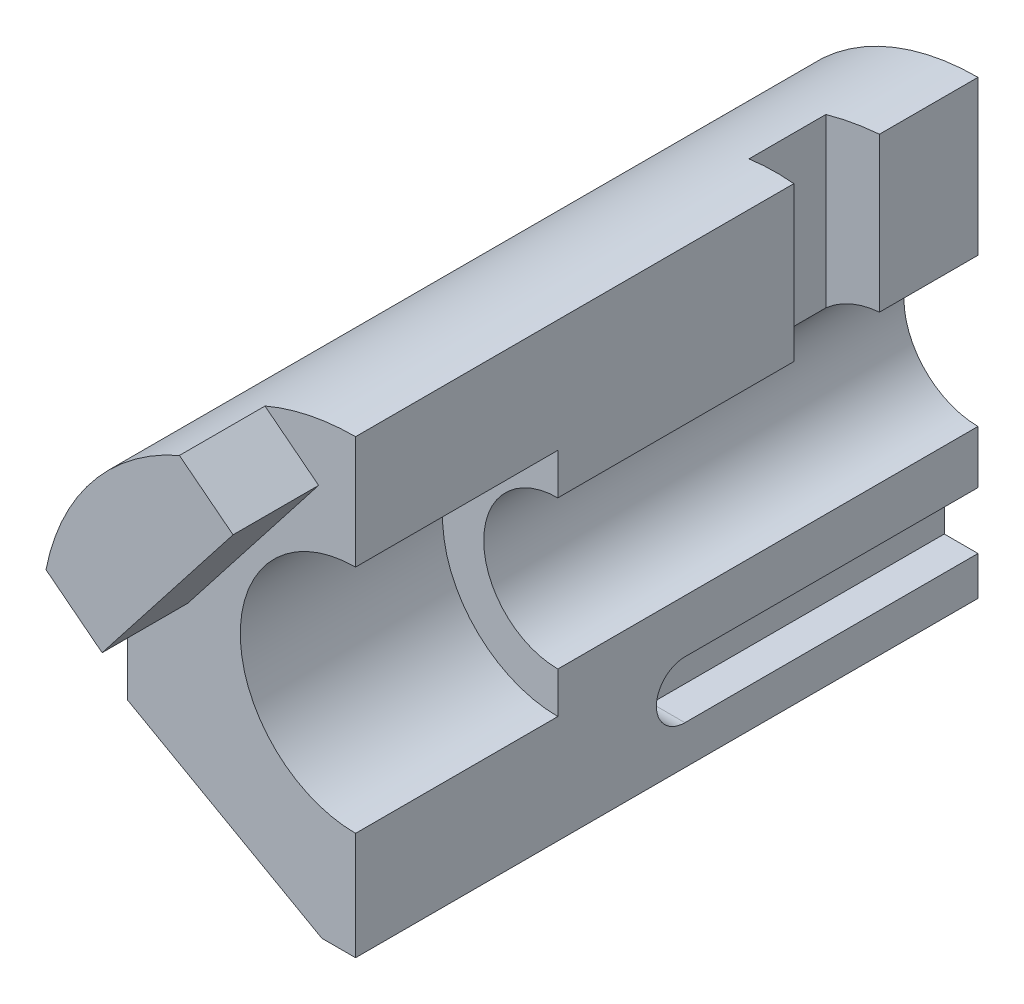
SolidWorks part; units mm, degrees
material "Alliage 1060"
ref_plane "Plan de face" through (0, 0, 0) normal (0, 0, 1) x (1, 0, 0)
ref_plane "Plan de dessus" through (0, 0, 0) normal (0, 1, 0) x (1, 0, 0)
ref_plane "Plan de droite" through (0, 0, 0) normal (1, 0, 0) x (0, 0, -1)
sketch "Esquisse1" plane through (0, 0, 0) normal (0, 0, 1) x (1, 0, 0)
  line L0 (0, -86) -> (0, 88)
  line L1 (0, -86) -> (-13, -86)
  line L5 (-88, 0) -> (-88, -43.8534)
  line L7 (-13, -86) -> (-88, -43.8534)
  arc A0 (0, 88) -> (-88, 0) centre (0, 0) ccw
  dimension "D1" = 176
  dimension "D2" = 13
extrude "Boss.-Extru.1" add sketch "Esquisse1" along normal blind 240
sketch "Esquisse2" plane through (0, 0, 240) normal (0, 0, 1) x (1, 0, 0)
  circle A0 centre (0, 0) radius 44.45
extrude "Enlèv. mat.-Extru.1" cut sketch "Esquisse2" against normal blind 78
sketch "Esquisse3" plane through (0, 0, 162) normal (0, 0, 1) x (1, 0, 0)
  line L0 (0, -44.45) -> (0, 44.45) construction
  circle A0 centre (0, 0) radius 28.575
extrude "Enlèv. mat.-Extru.2" cut sketch "Esquisse3" against normal through all
sketch "Esquisse7" plane through (0, 0, 240) normal (0, 0, 1) x (1, 0, 0)
  line L0 (0, 0) -> (-40.1885, 31.3987)
  line L1 (0, 0) -> (-155.8576, 0)
  line L2 (-14.2357, 64.6169) -> (-34.9181, 80.7758)
  line L3 (-64.7199, 0) -> (-14.2357, 64.6169)
  line L4 (-64.7199, 0) -> (-86.3605, 16.9075)
  arc A0 (0, 88) -> (-88, 0) centre (0, 0) ccw construction
  arc A1 (-34.9181, 80.7758) -> (-86.3605, 16.9075) centre (0, 0) ccw
  arc M5 (0, 88) -> (-88, 0) centre (0, 0) ccw
  dimension "D1" = 38
  dimension "D2" = 38
  dimension "D3" = 90
  dimension "D4" = 82
extrude "Boss.-Extru.4" add sketch "Esquisse7" along normal blind 33 contours L4 L3 L2 M5
sketch "Esquisse8" plane through (0, 0, 0) normal (1, 0, 0) x (0, 0, -1)
  line L0 (-71, 94.336) -> (-71, 4.336)
  line L3 (-71, 4.336) -> (-38, 4.336)
  line L4 (-38, 4.336) -> (-38, 94.336)
  line L5 (-38, 94.336) -> (-71, 94.336)
  line L6 (0, 28.575) -> (0, 88) construction
  dimension "D1" = 38
  dimension "D2" = 33
  dimension "D3" = 90
extrude "Enlèv. mat.-Extru.4" cut sketch "Esquisse8" against normal blind 19 draft 5 contours L5 L0 L3 L4
sketch "Esquisse9" plane through (0, 0, 0) normal (1, 0, 0) x (0, 0, -1)
  line L0 (0, -60) -> (-113, -60)
  line L1 (0, -86) -> (0, -28.575) construction
  line L2 (-240, -86) -> (0, -86) construction
  line L3 (-113, -49) -> (0, -49)
  line L4 (-113, -71) -> (0, -71)
  line L5 (0, -71) -> (0, -49)
  arc A0 (-113, -49) -> (-113, -71) centre (-113, -60) ccw
  dimension "D1" = 26
  dimension "D2" = 113
extrude "Enlèv. mat.-Extru.5" cut sketch "Esquisse9" against normal blind 13
ref_plane "Plan1" [suppressed] through (-9.5, 86.9622, 0) normal (-0.1086, 0.9941, 0) x (0.9941, 0.1086, 0)
sketch "Esquisse12" [suppressed] plane through (-9.5, 86.9622, 0) normal (-0.1086, 0.9941, 0) x (0.9941, 0.1086, 0)
  line L0 (9.5565, -38) -> (-9.5565, -39.6722)
  line L1 (-9.5565, -38) -> (-9.5565, -71) construction
  line L2 (9.5565, -71) -> (-9.5565, -69.3278)
  line L3 (-9.5565, -38) -> (9.5565, -38) construction
  line L4 (9.5565, -71) -> (-9.5565, -71) construction
  line L5 (-9.5565, -38) -> (9.5565, -38)
  line L6 (-9.5565, -38) -> (-9.5565, -39.6722)
  line L7 (9.5565, -71) -> (-9.5565, -71)
  line L8 (-9.5565, -69.3278) -> (-9.5565, -71)
  dimension "D1" = 5
  dimension "D2" = 5
sketch "Esquisse13" [suppressed] plane through (0, 0, 38) normal (0, 0, 1) x (1, 0, 0)
  line L2 (-19, 85.9244) -> (-19, 21.3432)
  line L3 (0, 28.575) -> (0, 88)
  line L4 (-19, 85.9244) -> (-19, 21.3432)
  line L5 (0, 28.575) -> (0, 88)
  arc A2 (0, 28.575) -> (-19, 21.3432) centre (0, 0) ccw
  arc A3 (0, 88) -> (-19, 85.9244) centre (0, 0) ccw
  arc A4 (0, 28.575) -> (-19, 21.3432) centre (0, 0) ccw
  arc A5 (0, 88) -> (-19, 85.9244) centre (0, 0) ccw
  dimension "D1" = 0
ref_plane "Plan2" [suppressed] through (0, 88, 0) normal (0, -1, 0) x (0, 0, -1)
sketch "Esquisse17" [suppressed] plane through (0, 88, 0) normal (0, -1, 0) x (0, 0, -1)
  line L0 (-71, -19) -> (-71, 0) construction
  line L1 (-38, 0) -> (-38, -19) construction
  line L2 (-38, -19) -> (-71, -19) construction
  line L3 (-71, -19) -> (-71, 0)
  line L4 (-38, 0) -> (-38, -19)
  line L5 (-38, -19) -> (-39.6623, -19)
  line L6 (-38, 0) -> (-39.6623, -19)
  line L7 (-71, 0) -> (-69.3377, -19)
  line L8 (-69.3377, -19) -> (-71, -19)
  dimension "D1" = 5
  dimension "D2" = 5
extrude "Boss.-Extru.5" [suppressed] add sketch "Esquisse17" along normal up to vertex (116.575 mm away) contours L4 L5 L6 | L3 L7 L8
sketch "Esquisse18" [suppressed] plane through (0, 0, 38) normal (0, 0, -1) x (-1, 0, 0)
  line L0 (0, 21.3432) -> (19, 21.3432) construction
  line L1 (0, 21.3432) -> (0, 28.575) construction
  line L2 (0, 21.3432) -> (19, 21.3432)
  line L3 (0, 21.3432) -> (0, 28.575)
  arc A0 (19, 21.3432) -> (0, 28.575) centre (0, 0) ccw construction
  arc A1 (19, 21.3432) -> (0, 28.575) centre (0, 0) ccw
extrude "Enlèv. mat.-Extru.6" [suppressed] cut sketch "Esquisse18" against normal through all
sketch "Esquisse19" [suppressed] plane through (0, 0, 38) normal (0, 0, -1) x (-1, 0, 0)
  line L2 (19, 85.9244) -> (19, 88)
  line L3 (19, 88) -> (0, 88)
  line L4 (19, 85.9244) -> (19, 88)
  line L5 (19, 88) -> (0, 88)
  arc A1 (19, 85.9244) -> (0, 88) centre (0, 0) ccw
  arc A2 (19, 85.9244) -> (0, 88) centre (0, 0) ccw
  dimension "D1" = 0
extrude "Enlèv. mat.-Extru.7" [suppressed] cut sketch "Esquisse19" against normal through all
sketch "Esquisse4" plane through (0, 0, 235) normal (0, 0, 1) x (1, 0, 0)
  line L1 (-13, 86) -> (-114.9095, -19.0921)
  line L2 (-114.9095, -19.0921) -> (-114.9095, 86)
  line L3 (-114.9095, 86) -> (-13, 86)
  line L7 (-13, 86) -> (-13, -81.662)
  line L8 (-13, -81.662) -> (-0.0929, -81.662)
  line L9 (-0.0929, -81.662) -> (0, 86)
  line L10 (0, -86) -> (0, -44.45) construction
  line L11 (0, 86) -> (-13, 86)
  arc A1 (0, 86) -> (-65.567, -55.6504) centre (0, 0) ccw construction
  dimension "D1" = 13
equation "\"A\"= 240"
equation "\"B\"= 113"
equation "\"C\"= 88"
equation "\"D1@Esquisse1\"=\"C\"*2"
equation "\"D1@Boss.-Extru.1\"=\"A\""
equation "\"D\"= 5"
equation "\"D2@Esquisse9\"=\"B\""
